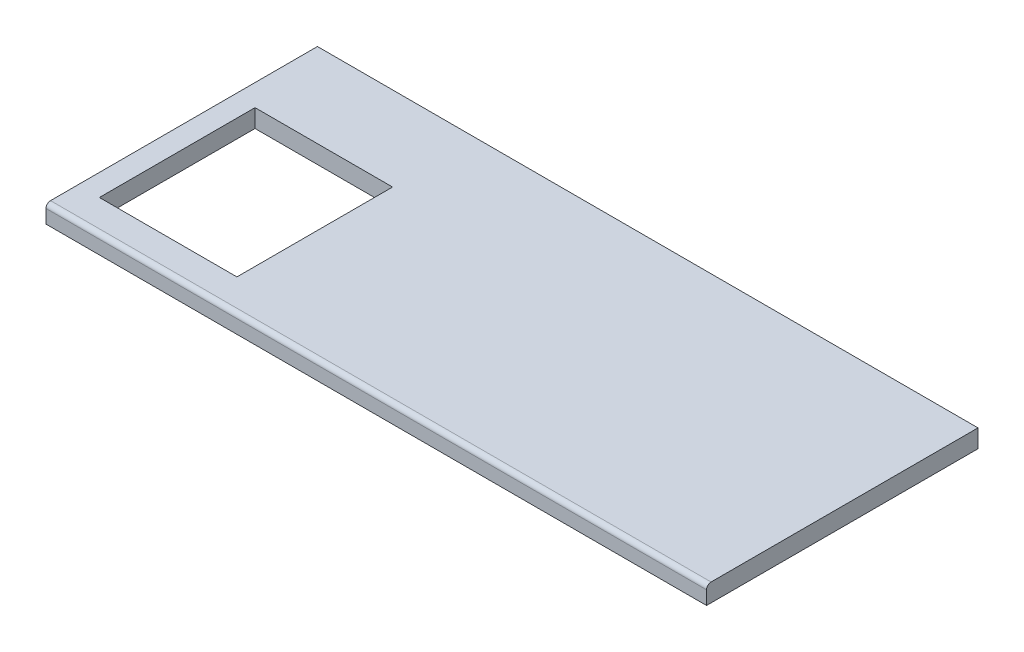
SolidWorks part; units mm, degrees
material "Maple"
ref_plane "Front Plane" through (0, 0, 0) normal (0, 0, 1) x (1, 0, 0)
ref_plane "Top Plane" through (0, 0, 0) normal (0, 1, 0) x (1, 0, 0)
ref_plane "Right Plane" through (0, 0, 0) normal (1, 0, 0) x (0, 0, -1)
sketch "Sketch1" plane through (0, 0, 0) normal (0, 1, 0) x (1, 0, 0)
  line L1 (-730, 300) -> (730, 300)
  line L2 (-730, 300) -> (-730, -300)
  line L3 (-730, -300) -> (730, -300)
  line L4 (730, 300) -> (730, -300)
  line L5 (-730, 300) -> (730, -300) construction
  line L6 (-730, -300) -> (730, 300) construction
  point P0 (0, 0)
  dimension "D1" = 1460
  dimension "D2" = 600
extrude "Boss-Extrude1" add sketch "Sketch1" along normal blind 40
fillet "Fillet1" radius 10 1 edges at (0, 40, 300)
sketch "Sketch2" plane through (0, 40, 0) normal (0, 1, 0) x (1, 0, 0)
  line L0 (730, -300) -> (-730, -300) construction
  line L1 (-682, 114) -> (-378, 114)
  line L2 (-682, 114) -> (-682, -230)
  line L3 (-682, -230) -> (-378, -230)
  line L4 (-378, 114) -> (-378, -230)
  line L5 (-682, 114) -> (-378, -230) construction
  line L6 (-682, -230) -> (-378, 114) construction
  line L7 (-330, 127.5558) -> (-330, -49872.4442) construction
  line L9 (-730, 300) -> (-730, -290) construction
  line L10 (-730, -58) -> (-330, -58) construction
  point P0 (-530, -58)
  point P13 (-530, -58)
  dimension "D1" = 304
  dimension "D2" = 344
  dimension "D3" = 70
  dimension "D4" = 400
extrude "Cut-Extrude1" cut sketch "Sketch2" against normal up to next
